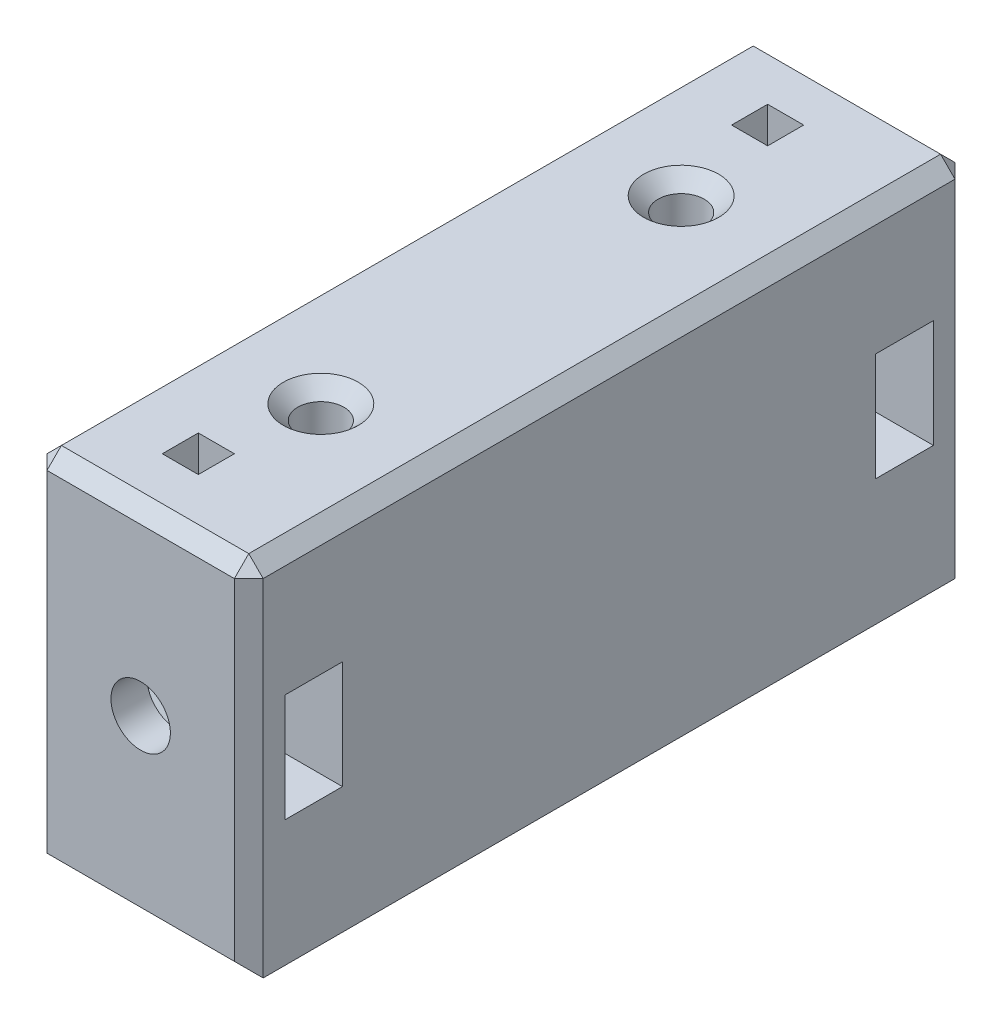
SolidWorks part; units mm, degrees
ref_plane "Front Plane" through (0, 0, 0) normal (1, 0, 0) x (0, 1, 0)
ref_plane "Top Plane" through (0, 0, 0) normal (0, 0, 1) x (0, 1, 0)
ref_plane "Right Plane" through (0, 0, 0) normal (0, 1, 0) x (-1, 0, 0)
sketch "Sketch1" plane through (0, 0, 0) normal (1, 0, 0) x (0, 1, 0)
  line L1 (25, 50) -> (-25, 50)
  line L2 (25, 50) -> (25, -50)
  line L3 (25, -50) -> (-25, -50)
  line L4 (-25, 50) -> (-25, -50)
  line L5 (25, 50) -> (-25, -50) construction
  line L6 (25, -50) -> (-25, 50) construction
  point P0 (0, 0)
  dimension "D1" = 50
  dimension "D2" = 100
extrude "Boss-Extrude1" add sketch "Sketch1" along normal blind 30
sketch "Sketch2" plane through (0, 25, 0) normal (0, 1, 0) x (-1, 0, 0)
  line L0 (-15, 25) -> (-15, -25) construction
  line L1 (0, 0) -> (-15, 0) construction
  line L2 (0, -50) -> (0, 50) construction
  circle A0 centre (-15, -25) radius 3.2
  circle A1 centre (-15, 25) radius 3.2
  point P3 (-15, 0)
  dimension "D3" = 6.4
  dimension "D1" = 15
  dimension "D2" = 50
extrude "Cut-Extrude1" cut sketch "Sketch2" against normal through all both and the other way through all
chamfer "Chamfer1" distance 2 angle 45 14 edges at (0, 25, 0) (15, 25, -50) (0, 0, 50) (15, 25, 50) (15, -25, 50) (30, 0, 50) (30, 25, 0) (0, 0, -50) (15, -25, -50) (30, 0, -50) (15, -25, -21.8) (15, -25, 21.8)
sketch "Sketch3" plane through (0, 0, 50) normal (0, 0, 1) x (1, 0, 0)
  line L0 (28, 23) -> (2, -23) construction
  line L2 (21.4952, 3.75) -> (15, 7.5)
  line L3 (15, 7.5) -> (8.5048, 3.75)
  line L4 (8.5048, 3.75) -> (8.5048, -3.75)
  line L5 (8.5048, -3.75) -> (15, -7.5)
  line L6 (15, -7.5) -> (21.4952, -3.75)
  line L7 (21.4952, -3.75) -> (21.4952, 3.75)
  line L8 (30.2926, -7.5) -> (-0.2926, -7.5)
  line L9 (30.2926, -7.5) -> (30.2926, 7.5)
  line L10 (30.2926, 7.5) -> (-0.2926, 7.5)
  line L11 (-0.2926, -7.5) -> (-0.2926, 7.5)
  line L12 (30.2926, -7.5) -> (-0.2926, 7.5) construction
  line L13 (30.2926, 7.5) -> (-0.2926, -7.5) construction
  circle A0 centre (15, 0) radius 6.4952 construction
  line M14 (28, -23) -> (28, 23)
  dimension "D1" = 15
extrude "Cut-Extrude2" cut sketch "Sketch3" against normal blind 8 from offset 5 contours L10 L2 L7 L6 L8 M14 | L9 L10 L8 M14 | L6 L7 L2 L3 L4 L5 offset against normal yes
sketch "Sketch4" plane through (0, 0, 50) normal (0, 0, 1) x (1, 0, 0)
  circle A0 centre (15, 0) radius 4.125
  dimension "D1" = 8.25
extrude "Cut-Extrude3" cut sketch "Sketch4" against normal blind 8
sketch "Sketch6" plane through (0, 7.5, 0) normal (0, -1, 0) x (1, 0, 0)
  line L1 (10, 42) -> (20, 42)
  line L2 (10, 42) -> (10, 37)
  line L3 (10, 37) -> (20, 37)
  line L4 (30, 45) -> (15, 45)
  line L5 (15, 45) -> (15, 37)
  line L6 (15, 37) -> (30, 37)
  line L7 (30, 37) -> (30, 45)
  line L8 (30, 45) -> (15, 45)
  line L9 (15, 45) -> (15, 37)
  line L10 (15, 37) -> (30, 37)
  line L11 (30, 37) -> (30, 45)
  line L12 (20, 42) -> (20, 37)
  line L13 (10, 42) -> (20, 37) construction
  line L14 (10, 37) -> (20, 42) construction
  point P2 (15, 39.5)
  line M8 (15, 45) -> (15, 37)
  dimension "D2" = 5
  dimension "D3" = 10
  dimension "D1" = 0
extrude "Cut-Extrude4" cut sketch "Sketch6" against normal through all both and the other way through all contours L2 L3 L1 M8
mirror "Mirror1" about plane through (0, 0, 0) normal (0, 0, 1) of "Cut-Extrude2", "Cut-Extrude3", "Cut-Extrude4"
